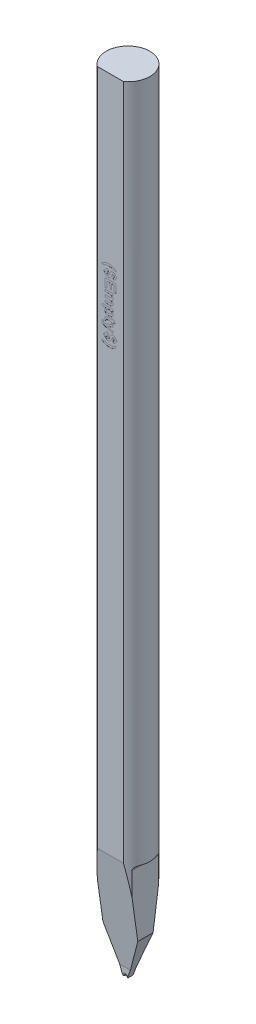
SolidWorks part; units mm, degrees
ref_plane "Ebene vorne" through (0, 0, 0) normal (0, 0, 1) x (1, 0, 0)
ref_plane "Ebene oben" through (0, 0, 0) normal (0, 1, 0) x (1, 0, 0)
ref_plane "Ebene rechts" through (0, 0, 0) normal (1, 0, 0) x (0, 0, -1)
sketch "sketch_TL_cutting" plane through (0, 0, 0) normal (0, 1, 0) x (1, 0, 0)
  circle A0 centre (0, 0) radius 1.9977
extrude "TL_cutting" add sketch "sketch_TL_cutting" along normal blind 72.009
sketch "sketch_TDF_grinding" plane through (0, 0, 0) normal (0, 1, 0) x (1, 0, 0)
  line L0 (0, 0) -> (0, -1.6015) construction
  line L1 (-2.0077, -5.6169) -> (2.0077, -5.6169)
  line L2 (-2.0077, -5.6169) -> (-2.0077, -1.6015)
  line L3 (-2.0077, -1.6015) -> (2.0077, -1.6015)
  line L4 (2.0077, -5.6169) -> (2.0077, -1.6015)
  circle A1 centre (0, 0) radius 1.9977 construction
  point P9 (0, -5.6169)
  dimension "TD_2Offset_X" = 4.0154
  dimension "TD_2Offset_Z" = 4.0154
extrude "TDF_grinding" cut sketch "sketch_TDF_grinding" along normal through all
sketch "sketch_engraving" plane through (0, 0, 1.6015) normal (0, 0, 1) x (1, 0, 0)
  line L0 (1.1942, 72.009) -> (-1.1942, 72.009) construction
  line L6 (-1.1942, 0) -> (1.1942, 0) construction
  line L7 (0, 0) -> (0, 57.009) construction
  line L8 (-0.5, 57.009) -> (-0.5, 0) construction
  text T0 "($Empty$)" font "Arial" height 1
  dimension "D2" = 0.5
  dimension "EngravingStart" = 15
extrude "engraving" cut sketch "sketch_engraving" against normal blind 0.005
sketch "sketch_VW_VR_grinding" plane through (0, 0, 0) normal (0, 0, 1) x (1, 0, 0)
  line L0 (-1.59, -0.01) -> (-1.59, 9.682)
  line L1 (1.59, -0.01) -> (1.59, 9.682)
  line L2 (-1.59, 0) -> (1.59, 0) construction
  line L3 (-2.0077, 10) -> (-1.908, 10)
  line L4 (1.908, 10) -> (2.0077, 10)
  line L5 (-2.0077, 10) -> (-2.0077, -0.01)
  line L6 (-2.0077, -0.01) -> (-1.59, -0.01)
  line L7 (1.59, -0.01) -> (2.0077, -0.01)
  line L8 (2.0077, -0.01) -> (2.0077, 10)
  line L9 (-1.908, 10) -> (-1.908, 9.682) construction
  line L10 (-1.59, 9.682) -> (-1.908, 9.682) construction
  line L11 (1.59, 9.682) -> (1.908, 9.682) construction
  line L12 (1.908, 10) -> (1.908, 9.682) construction
  arc A0 (-1.908, 10) -> (-1.59, 9.682) centre (-1.908, 9.682) cw
  arc A2 (1.59, 9.682) -> (1.908, 10) centre (1.908, 9.682) cw
  dimension "D2" = 0.318
  dimension "D1" = 0.01
  dimension "D4" = 4.0154
extrude "VW_VR_grinding" cut sketch "sketch_VW_VR_grinding" against normal blind 2.0077 and the other way blind 2.0077
sketch "sketch_ISA_grinding" plane through (0, 0, 0) normal (0, 0, 1) x (1, 0, 0)
  line L0 (-0.1994, 0) -> (-2.0077, 4.9683)
  line L4 (2.0077, 4.9683) -> (0.1994, 0)
  line L5 (0.1994, 0) -> (-0.1994, 0)
  line L6 (0, 0) -> (0, 30.49) construction
  line L7 (-2.0077, 4.9683) -> (-2.0077, -0.01)
  line L12 (-2.0077, -0.01) -> (2.0077, -0.01)
  line L13 (2.0077, -0.01) -> (2.0077, 4.9683)
  dimension "ISA" = 40
  dimension "TD_2Offset" = 4.0154
  dimension "Offset" = 0.01
extrude "ISA_grinding" cut sketch "sketch_ISA_grinding" against normal blind 2.0077 and the other way blind 2.0077
sketch "sketch_pre_FRX_BRX" plane through (0, 0, 0) normal (1, 0, 0) x (0, 0, -1)
  line L0 (1.9977, -0.01) -> (1.9977, 3.9152) construction
  line L1 (-1.6015, -0.01) -> (-1.6015, 0.7799) construction
  line L2 (-0.2705, -0.01) -> (-0.2705, 0.7799)
  line L3 (-0.2705, 0.7799) -> (-2.0077, 0.7799)
  line L4 (-2.0077, 0.7799) -> (-2.0077, -0.01)
  line L5 (-2.0077, -0.01) -> (-0.2705, -0.01)
  line L6 (0.2705, -0.01) -> (0.2705, 0.7799)
  line L7 (0.2705, 0.7799) -> (2.0077, 0.7799)
  line L8 (2.0077, 0.7799) -> (2.0077, -0.01)
  line L9 (2.0077, -0.01) -> (0.2705, -0.01)
  dimension "D3" = 0.01
  dimension "D4" = 0.7899
  dimension "D5" = 4.0154
  dimension "D6" = 0.541
  dimension "D2" = 0.01
  dimension "D7" = 2.2682
extrude "pre_FRX_BRX" cut sketch "sketch_pre_FRX_BRX" against normal blind 2.0077 and the other way blind 2.0077
sketch "sketch_contour_V-Groove" plane through (0, 0, 0) normal (1, 0, 0) x (0, 0, -1)
  line L0 (-1.6015, 0.1118) -> (0, 0.1118)
  line L1 (0, 0.1118) -> (1.9977, 0.1118)
  line L2 (1.9977, -0.8411) -> (1.9977, 1.3178) construction
  line L3 (-1.6015, -0.9209) -> (-1.6015, 1.9363) construction
  line L4 (-1.6015, 0) -> (1.9977, 0) construction
  line L5 (0.2705, 0) -> (0.2705, 0.1118) construction
  line L6 (-0.2705, 0) -> (-0.2705, 0.1118) construction
  dimension "D1" = 0
ref_plane "front" through (0, 0, 1.6015) normal (0, 0, 1) x (1, 0, 0)
ref_plane "back" through (0, 0, -1.9977) normal (0, 0, 1) x (1, 0, 0)
sketch "sketch_section_V-Groove" plane through (0, 0, 1.6015) normal (0, 0, 1) x (1, 0, 0)
  line L0 (-1.2395, -1.1176) -> (-0.0173, 0.1046)
  line L2 (0.0173, 0.1046) -> (1.2395, -1.1176)
  line L3 (-1.2395, -1.1176) -> (1.2395, -1.1176)
  line L4 (0, -1.1176) -> (0, 0.1118) construction
  line L5 (-0.1219, 0) -> (0.1219, 0) construction
  arc A0 (0.0173, 0.1046) -> (-0.0173, 0.1046) centre (0, 0.0872) ccw
  dimension "GA" = 90
sweep "V-Groove_EDM" cut profiles "sketch_section_V-Groove" path "sketch_contour_V-Groove"
fillet "FR_EDM" radius 0.2007 3 edges at (0.0696, 0.0523, 0.2705) (0, 0.1118, 0.2705) (-0.0696, 0.0523, 0.2705)
fillet "BR_EDM" radius 0.0991 3 edges at (0.0696, 0.0523, -0.2705) (0, 0.1118, -0.2705) (-0.0696, 0.0523, -0.2705)
sketch "sketch_FA_BA_grinding" plane through (0, 0, 0) normal (1, 0, 0) x (0, 0, -1)
  line L2 (2.9977, 20.195) -> (2.9977, -0.1)
  line L3 (2.9977, -0.1) -> (0.2705, -0.1)
  line L5 (0.2705, -0.1) -> (0.2705, 0.7899)
  line L6 (0.2705, 0.7899) -> (2.9977, 20.195)
  line L7 (1.9977, -0.1) -> (1.9977, 13.0796) construction
  line L8 (-1.6015, 10.2602) -> (-1.6015, -0.1) construction
  line L9 (-3.2182, 21.764) -> (-0.2705, 0.7899)
  line L10 (-0.2705, 0.7899) -> (-0.2705, -0.1)
  line L11 (-0.2705, -0.1) -> (-3.2182, -0.1)
  line L12 (-3.2182, -0.1) -> (-3.2182, 21.764)
  line L13 (-0.2705, 0.7899) -> (0.2705, 0.7899) construction
  dimension "D4" = 1
  dimension "D1" = 0.1
  dimension "FA" = 8
  dimension "BA" = 8
extrude "FA_BA_grinding" cut sketch "sketch_FA_BA_grinding" against normal blind 2.0077 and the other way blind 2.0077
sketch "sketch_groove_dimensions" plane through (0, 0, 0) normal (1, 0, 0) x (0, 0, -1)
  line L0 (-0.0698, 0.1118) -> (0.1715, 0.1118)
  line L1 (-0.2705, 0) -> (-0.2705, 0.3124) construction
  line L2 (1.9977, 0) -> (1.9977, 0.4166) construction
  line L3 (0.2705, 0) -> (0.2705, 0.2108) construction
  line L4 (-1.6015, 0) -> (-1.6015, 0.3999) construction
  arc A0 (0.1715, 0.1118) -> (0.2705, 0.2108) centre (0.1715, 0.2108) ccw
  arc A1 (-0.0698, 0.1118) -> (-0.2705, 0.3124) centre (-0.0698, 0.3124) cw
equation "\"_Offset\"=0.01mm"
equation "\"TL\"=72.009mm"
equation "\"TD\"=3.99542mm"
equation "\"TDF\"=3.59918mm"
equation "\"BA\"=8deg"
equation "\"ISA\"=40deg"
equation "\"FA\"=8deg"
equation "\"GR\"=0.0254mm"
equation "\"GA\"=90deg"
equation "\"GD\"=0.11176mm"
equation "\"FL\"=0.54102mm"
equation "\"F\"=0.23876mm"
equation "\"FX\"=0mm"
equation "\"B\"=0.24384mm"
equation "\"VW\"=3.18008mm"
equation "\"cleaned_VR\"= IIF ( \"VR\" > 0 , \"VR\" , \"E\" - \"_Offset\" )"
equation "\"cleaned_VW\"= IIF ( \"VW\" > 0 , \"VW\" , \"TD\" - \"_Offset\" )"
equation "\"back_edge\"= \"TD\" / 2 - \"X\""
equation "\"side_edge_Offset\"= \"TD\" / 2 + \"_Offset\""
equation "\"TD@sketch_TL_cutting\"=\"TD\""
equation "\"TL@TL_cutting\"=\"TL\""
equation "\"TDF@sketch_TDF_grinding\"=\"TDF\""
equation "\"TD_2Offset_X@sketch_TDF_grinding\"=\"TD\"+2*\"_Offset\""
equation "\"TD_2Offset_Z@sketch_TDF_grinding\"=\"TD\"+2*\"_Offset\""
equation "\"TL_Offset\"= \"TL\" + \"_Offset\""
equation "\"ISA@sketch_ISA_grinding\"=\"ISA\""
equation "\"W@sketch_ISA_grinding\"=\"W\""
equation "\"TD_2Offset@sketch_ISA_grinding\"=\"TD\"+2*\"_Offset\""
equation "\"Offset@sketch_ISA_grinding\"=\"_Offset\""
equation "\"05TD_Offset_posZ@ISA_grinding\"=\"side_edge_Offset\""
equation "\"05TD_Offset_negZ@ISA_grinding\"=\"side_edge_Offset\""
equation "\"E\"=0.78994mm"
equation "\"cleaned_X\"= IIF ( \"X\" > 0 , \"X\" , \"TD\" / 2 - \"FL\" / 2 )"
equation "\"FR\"=0.20066mm"
equation "\"BR\"=0.09906mm"
equation "\"D1\"= \"side_edge_Offset\""
equation "\"D2\"= \"side_edge_Offset\""
equation "\"TDF@sketch_FA_BA_grinding\" = \"TDF\""
equation "\"FL@sketch_FA_BA_grinding\"=\"FL\""
equation "\"E@sketch_FA_BA_grinding\" = \"E\""
equation "\"D1@FA_BA_grinding\"=\"side_edge_Offset\""
equation "\"D2@FA_BA_grinding\"=\"side_angle_Offset\""
equation "\"10GD@sketch_section_V-Groove\" = 10 * \"GD\""
equation "\"GA@sketch_section_V-Groove\" = \"GA\""
equation "\"GD@sketch_section_V-Groove\" = \"GD\""
equation "\"B@sketch_section_V-Groove\" = \"B\""
equation "\"GD@sketch_contour_V-Groove\" = \"GD\""
equation "\"cleaned_FRX\"= IIF ( \"FRX\" > 0 , \"FRX\" , \"FR\" )"
equation "\"cleaned_BRX\"= IIF ( \"BRX\" > 0 , \"BRX\" , \"BR\" )"
equation "\"FL_groove_angle\"=0deg"
equation "\"D3@sketch_pre_FRX_BRX\" = \"_Offset\""
equation "\"D4@sketch_pre_FRX_BRX\" = \"E\""
equation "\"D5@sketch_pre_FRX_BRX\" = 2 * \"side_edge_Offset\""
equation "\"D6@sketch_pre_FRX_BRX\" = \"FL\" + ( \"FR\" - \"cleaned_FRX\" ) + ( \"BR\" - \"cleaned_BRX\" )"
equation "\"TD/2@sketch_pre_FRX_BRX\" = \"TD\" / 2"
equation "\"TDF@sketch_pre_FRX_BRX\" = \"TDF\""
equation "\"D2@sketch_pre_FRX_BRX\" = \"_Offset\""
equation "\"D1@pre_FRX_BRX\" = \"side_edge_Offset\""
equation "\"D2@pre_FRX_BRX\" = \"side_edge_Offset\""
equation "\"D1@BR_EDM\"=\"BR\""
equation "\"TD/2@sketch_FA_BA_grinding\" = \"TD\" / 2"
equation "\"TD/2@sketch_contour_V-Groove\" = \"TD\" / 2"
equation "\"TDF@sketch_contour_V-Groove\" = \"TDF\""
equation "\"D1@sketch_contour_V-Groove\"=\"FL_groove_angle\""
equation "\"FL@sketch_contour_V-Groove\"=\"FL\""
equation "\"FL/2@sketch_contour_V-Groove\" = \"FL\" / 2"
equation "\"D1@FR_EDM\"=\"FR\""
equation "\"D1@sketch_VW_VR_grinding\" = \"_Offset\""
equation "\"D4@sketch_VW_VR_grinding\" = 2 * \"side_edge_Offset\""
equation "\"VR@sketch_VW_VR_grinding\" = \"cleaned_VR\""
equation "\"VW@sketch_VW_VR_grinding\"=\"cleaned_VW\""
equation "\"D1@VW_VR_grinding\" = \"side_edge_Offset\""
equation "\"D2@VW_VR_grinding\" = \"side_edge_Offset\""
equation "\"X\"=0.94996mm"
equation "\"VR\"=9.99998mm"
equation "\"W\"=0.39878mm"
equation "\"VW_radius\"= \"cleaned_VW\" / 10"
equation "\"VW_radius_cleaned\"= IIF ( \"VW\" > 0 , \"VW_radius\" , \"_Offset\" / 2 )"
equation "\"D2@sketch_VW_VR_grinding\"=\"VW_radius_cleaned\""
equation "\"FRX\"=0mm"
equation "\"BRX\"=0mm"
equation "\"FA@sketch_FA_BA_grinding\" = \"FA\""
equation "\"D4@sketch_FA_BA_grinding\"=\"_Offset\"*100"
equation "\"BA@sketch_FA_BA_grinding\" = \"BA\""
equation "\"D1@sketch_groove_dimensions\" = \"TD\" / 2"
equation "\"FL@sketch_groove_dimensions\" = \"FL\""
equation "\"FR@sketch_groove_dimensions\" = \"FR\""
equation "\"BR@sketch_groove_dimensions\" = \"BR\""
equation "\"FRX@sketch_groove_dimensions\" = \"cleaned_FRX\""
equation "\"BRX@sketch_groove_dimensions\" = \"cleaned_BRX\""
equation "\"GD@sketch_groove_dimensions\" = \"GD\""
equation "\"cleaned_FX\"= IIF ( \"FX\" > 0 , \"FX\" , \"TDF\" - ( \"TD\" + \"FL\" ) / 2 )"
equation "\"D7@sketch_pre_FRX_BRX\"=\"TDF\"-\"cleaned_FX\"-(\"FR\"-\"cleaned_FRX\")"
equation "\"FX@sketch_contour_V-Groove\" = \"cleaned_FX\""
equation "\"FX@sketch_FA_BA_grinding\" = \"cleaned_FX\""
equation "\"TDF@sketch_groove_dimensions\" = \"TDF\""
equation "\"FX@sketch_groove_dimensions\" = \"cleaned_FX\""
equation "\"EngravingStart\"=15mm"
equation "\"EngravingStart@sketch_engraving\" = \"EngravingStart\""
